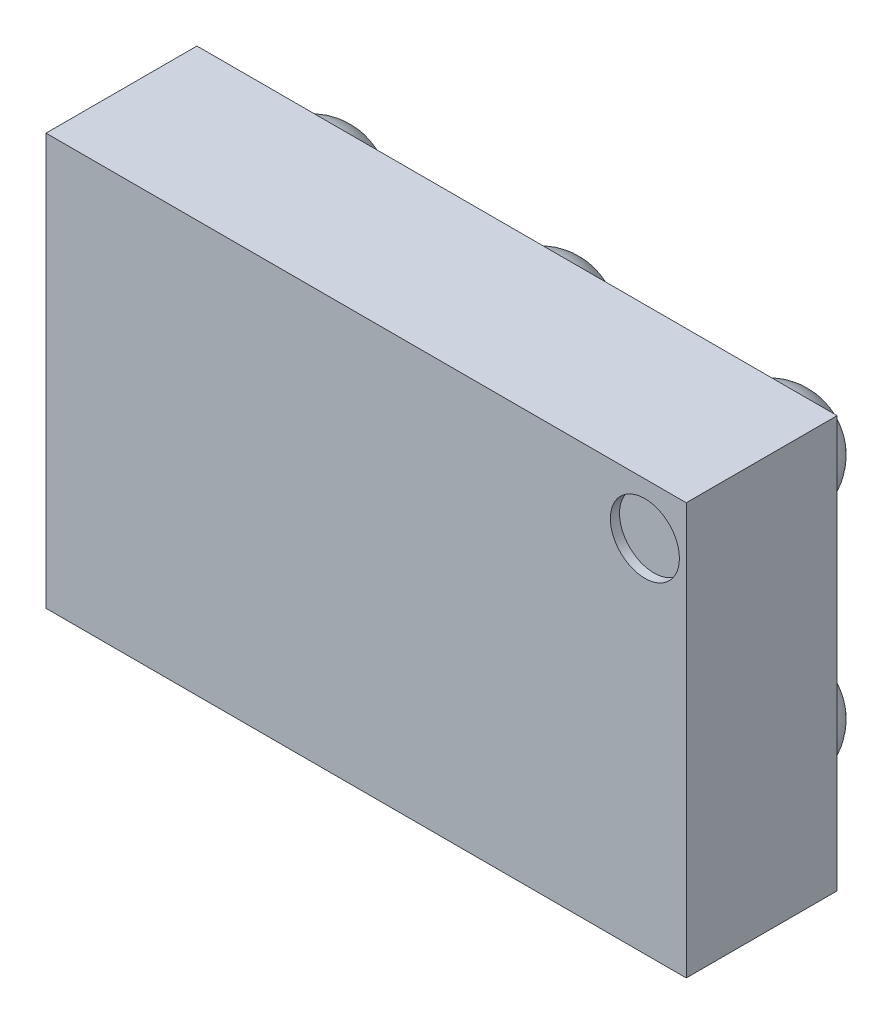
SolidWorks part; units mm, degrees
ref_plane "Front Plane" through (0, 0, 0) normal (0, 0, 1) x (1, 0, 0)
ref_plane "Top Plane" through (0, 0, 0) normal (0, 1, 0) x (1, 0, 0)
ref_plane "Right Plane" through (0, 0, 0) normal (1, 0, 0) x (0, 0, -1)
sketch "Sketch1" plane through (0, 0, 0) normal (0, 0, 1) x (1, 0, 0)
  line L1 (-0.7, -0.45) -> (0.7, -0.45)
  line L2 (-0.7, -0.45) -> (-0.7, 0.45)
  line L3 (-0.7, 0.45) -> (0.7, 0.45)
  line L4 (0.7, -0.45) -> (0.7, 0.45)
  line L5 (-0.7, -0.45) -> (0.7, 0.45) construction
  line L6 (-0.7, 0.45) -> (0.7, -0.45) construction
  point P0 (0, 0)
  dimension "D1" = 1.4
  dimension "D2" = 0.9
extrude "Boss-Extrude1" add sketch "Sketch1" along normal blind 0.33 from offset 0.17
ref_plane "Plane1" through (0, 0.25, 0) normal (0, 1, 0) x (1, 0, 0)
sketch "Sketch2" plane through (0, 0.25, 0) normal (0, 1, 0) x (1, 0, 0)
  line L1 (0.7, -0.17) -> (-0.7, -0.17) construction
  line L2 (-0.5, 0) -> (-0.5, -0.24)
  arc A0 (-0.5, 0) -> (-0.5, -0.24) centre (-0.5, -0.12) ccw
  dimension "D3" = 0.17
  dimension "D1" = 0.12
  dimension "D2" = 0.5
revolve "Revolve1" add sketch "Sketch2" angle 360 about L2
pattern_linear "LPattern1" count 3 spacing 0.5 along (1, 0, 0) count 2 spacing 0.5 along (0, -1, 0) of "Revolve1"
sketch "Sketch3" plane through (0, 0, 0.5) normal (0, 0, 1) x (1, 0, 0)
  circle A0 centre (0.6095, 0.3372) radius 0.0755
extrude "Cut-Extrude1" cut sketch "Sketch3" against normal blind 0.02
